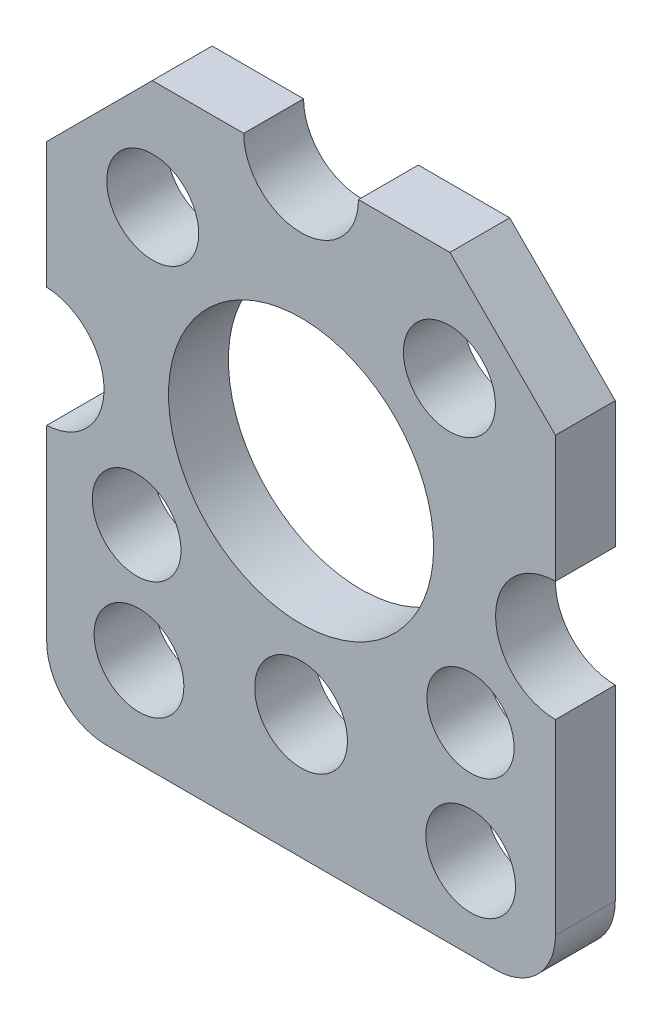
SolidWorks part; units mm, degrees
ref_plane "Front Plane" through (0, 0, 0) normal (0, 0, 1) x (1, 0, 0)
ref_plane "Top Plane" through (0, 0, 0) normal (0, 1, 0) x (1, 0, 0)
ref_plane "Right Plane" through (0, 0, 0) normal (1, 0, 0) x (0, 0, -1)
sketch "Sketch1" plane through (0, 0, 0) normal (0, 0, 1) x (1, 0, 0)
  line L1 (-23.1938, 17.415) -> (-1.6038, 17.415)
  line L2 (-23.1938, 17.415) -> (-23.1938, -7.985)
  line L3 (-23.1938, -7.985) -> (-1.6038, -7.985)
  line L4 (-1.6038, 17.415) -> (-1.6038, -7.985)
extrude "Boss-Extrude1" add sketch "Sketch1" along normal blind 2.54 contours L2 L1 L4 L3
fillet "Fillet1" radius 2.54 2 edges at (-1.6038, -7.985, 1.27) (-23.1938, -7.985, 1.27)
sketch "Sketch2" plane through (0, 0, 2.54) normal (0, 0, 1) x (1, 0, 0)
  line L0 (-12.3988, 17.415) -> (-12.3988, 6.9742) construction
  line L1 (-23.1938, 17.415) -> (-1.6038, 17.415) construction
  line L2 (-24.2672, 11.8611) -> (-17.4108, 18.7174)
  line L3 (-17.4108, 18.7174) -> (-24.2672, 18.7174)
  line L4 (-24.2672, 18.7174) -> (-24.2672, 11.8611)
  line L5 (-7.3868, 18.7174) -> (-0.5304, 18.7174)
  line L6 (-0.5304, 11.8611) -> (-7.3868, 18.7174)
  line L7 (-0.5304, 18.7174) -> (-0.5304, 11.8611)
extrude "Cut-Extrude1" cut sketch "Sketch2" against normal through all
sketch "Sketch3" plane through (0, 0, 2.54) normal (0, 0, 1) x (1, 0, 0)
  line L0 (-12.3988, 17.415) -> (-12.3988, 5.0406) construction
  line L1 (-18.7133, 17.415) -> (-6.0844, 17.415) construction
  line L2 (-12.3988, 5.0406) -> (-25.3554, 5.0406) construction
  line L4 (-1.6038, 12.9344) -> (-1.6038, -5.445) construction
  circle A0 centre (-12.3988, 6.226) radius 5.6255
  circle A2 centre (-23.3017, 5.0406) radius 2.54
  circle A3 centre (-1.6038, 5.0239) radius 2.5405
  circle A4 centre (-18.6934, 12.7711) radius 1.9513
  circle A5 centre (-12.3988, 17.415) radius 2.4343
  circle A6 centre (-6.1042, 12.7711) radius 1.9513
  circle A7 centre (-12.3988, -2.7234) radius 1.9689
  circle A8 centre (-19.2778, -4.1747) radius 1.905
  circle A9 centre (-5.2025, -4.5086) radius 1.905
extrude "Cut-Extrude2" cut sketch "Sketch3" against normal through all
sketch "Sketch4" plane through (0, 0, 2.54) normal (0, 0, 1) x (1, 0, 0)
  circle A0 centre (-19.3771, 0.7561) radius 1.883
  circle A1 centre (-5.209, 0.5658) radius 1.8515
extrude "Cut-Extrude3" cut sketch "Sketch4" against normal through all contours A1 | A0
